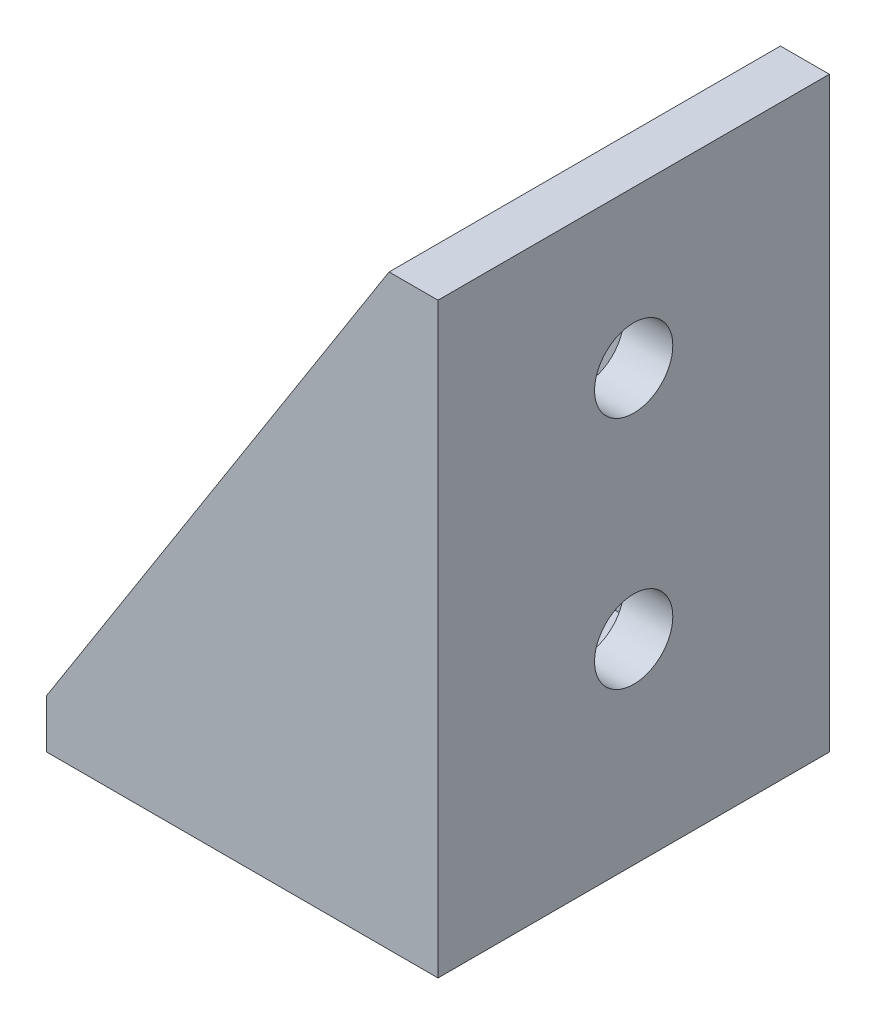
SolidWorks part; units mm, degrees
material "聚脂树脂"
ref_plane "前视基准面" through (0, 0, 0) normal (0, 0, 1) x (1, 0, 0)
ref_plane "上视基准面" through (0, 0, 0) normal (0, 1, 0) x (1, 0, 0)
ref_plane "右视基准面" through (0, 0, 0) normal (1, 0, 0) x (0, 0, -1)
other "Configuration Table"
sketch "草图1" plane through (0, 0, 0) normal (0, 0, 1) x (1, 0, 0)
  line L0 (0, 0) -> (20, 0)
  line L1 (20, 0) -> (20, 30)
  line L2 (20, 30) -> (17.5, 30)
  line L3 (17.5, 30) -> (0, 2.5)
  line L4 (0, 2.5) -> (0, 0)
  dimension "D1" = 30
  dimension "D2" = 2.5
  dimension "D3" = 20
extrude "凸台-拉伸1" add sketch "草图1" against normal blind 20
sketch "草图2" plane through (0, 0, 0) normal (0, 1, 0) x (1, 0, 0)
  line L0 (17.5, 20) -> (17.5, 0) construction
  line L1 (17.5, 18.3) -> (0, 18.3)
  line L2 (17.5, 18.3) -> (17.5, 1.7)
  line L3 (17.5, 1.7) -> (0, 1.7)
  line L4 (0, 18.3) -> (0, 1.7)
  line L5 (0, 20) -> (0, 0) construction
  line L6 (17.5, 20) -> (0, 20) construction
  line L7 (17.5, 0) -> (0, 0) construction
  dimension "D1" = 1.7
  dimension "D2" = 1.7
extrude "切除-拉伸1" cut sketch "草图2" against normal blind 27.5 from surface at 30 starting at face at (18.75, 30, -10)
sketch "草图3" plane through (0, 0, 0) normal (1, 0, 0) x (0, 0, -1)
  line L0 (10, -0.9294) -> (10, 20.6169) construction
  line L1 (20, 30) -> (0, 30) construction
  circle A0 centre (10, 22) radius 2
  circle A1 centre (10, 10) radius 2
  dimension "D1" = 4
  dimension "D2" = 10
  dimension "D3" = 12
  dimension "D4" = 8
extrude "切除-拉伸2" cut sketch "草图3" along normal up to next from surface
sketch "草图4" plane through (0, 0, 0) normal (0, 1, 0) x (1, 0, 0)
  line L0 (20, 20) -> (20, 0) construction
  circle A0 centre (9, 10) radius 1.7
  dimension "D3" = 3.4
  dimension "D1" = 10
  dimension "D2" = 11
extrude "切除-拉伸3" cut sketch "草图4" along normal up to next
